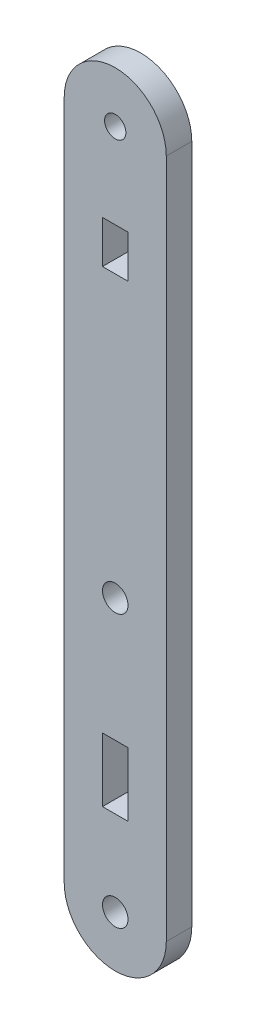
SolidWorks part; units mm, degrees
ref_plane "前基準面" through (0, 0, 0) normal (0, 0, 1) x (1, 0, 0)
ref_plane "上基準面" through (0, 0, 0) normal (0, 1, 0) x (1, 0, 0)
ref_plane "右基準面" through (0, 0, 0) normal (1, 0, 0) x (0, 0, -1)
sketch "草圖1" plane through (0, 0, 0) normal (0, 0, 1) x (1, 0, 0)
  line L0 (12.3003, 7.0001) -> (12.3003, 87.0001)
  line L1 (16.8003, 77.0001) -> (19.8003, 77.0001)
  line L2 (16.8003, 77.0001) -> (16.8003, 72.0001)
  line L3 (16.8003, 72.0001) -> (19.8003, 72.0001)
  line L4 (19.8003, 77.0001) -> (19.8003, 72.0001)
  line L5 (19.8003, 17.0001) -> (16.8003, 17.0001)
  line L6 (19.8003, 17.0001) -> (19.8003, 24.5001)
  line L7 (19.8003, 24.5001) -> (16.8003, 24.5001)
  line L8 (16.8003, 17.0001) -> (16.8003, 24.5001)
  line L9 (24.3003, 87.0001) -> (24.3003, 7)
  circle A0 centre (18.3003, 87.0001) radius 1.25
  circle A1 centre (18.3003, 87.0001) radius 1.25 construction
  arc A2 (12.3003, 87.0001) -> (24.3003, 87.0001) centre (18.3003, 87.0001) cw
  arc A3 (24.3003, 87.0001) -> (18.7997, 92.9793) centre (18.3003, 87.0001) ccw construction
  circle A4 centre (18.3003, 39) radius 1.5
  circle A5 centre (18.3003, 39) radius 1.5 construction
  circle A6 centre (18.3035, 7.0071) radius 1.5
  circle A7 centre (18.3035, 7.0071) radius 1.5 construction
  arc A8 (12.3003, 7.0001) -> (24.3003, 7) centre (18.3003, 7.0002) ccw
  arc A9 (12.3003, 7.0001) -> (24.3003, 7) centre (18.3003, 7.0002) ccw construction
extrude "填料-伸長1" add sketch "草圖1" along normal blind 3
